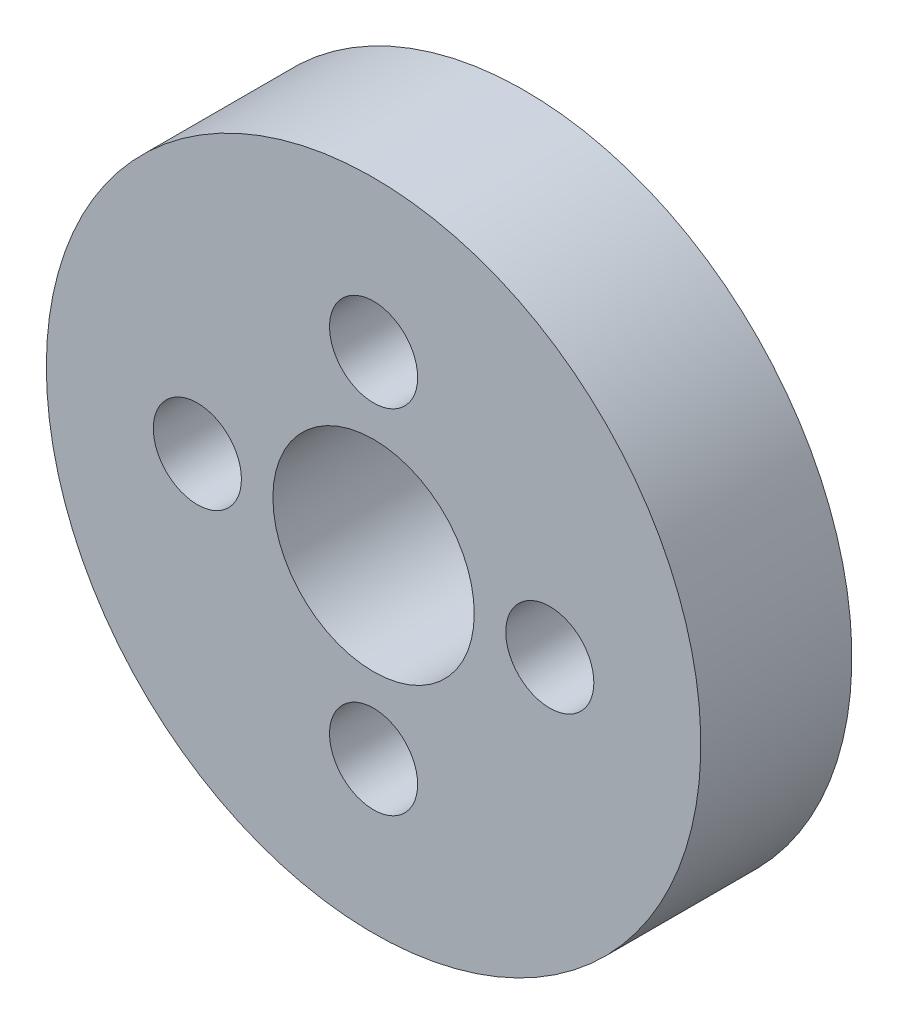
SolidWorks part; units mm, degrees
ref_plane "Front Plane" through (0, 0, 0) normal (0, 0, 1) x (1, 0, 0)
ref_plane "Top Plane" through (0, 0, 0) normal (0, 1, 0) x (1, 0, 0)
ref_plane "Right Plane" through (0, 0, 0) normal (1, 0, 0) x (0, 0, -1)
sketch "Sketch1" plane through (0, 0, 0) normal (0, 0, 1) x (1, 0, 0)
  circle A0 centre (0, 0) radius 10.3187
  circle A1 centre (0, 0) radius 3.175
extrude "Boss-Extrude1" add sketch "Sketch1" along normal blind 4.7625
sketch "Sketch6" plane through (0, 0, 4.7625) normal (0, 0, 1) x (1, 0, 0)
  circle A0 centre (0, 5.5562) radius 1.3891
  circle A1 centre (5.5563, 0) radius 1.3891
  circle A2 centre (0, -5.5562) radius 1.3891
  circle A3 centre (-5.5562, 0) radius 1.3891
  point P12 (0, 0)
  dimension "D1" = 5.5562
  dimension "D2" = 4
extrude "Cut-Extrude1" cut sketch "Sketch6" against normal through all
